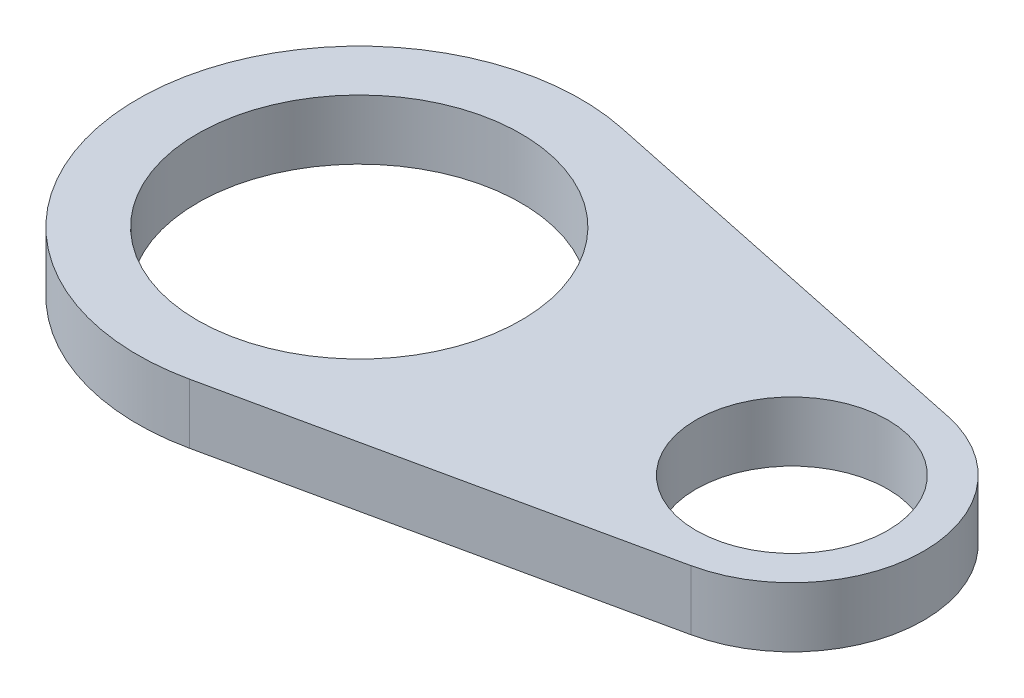
SolidWorks part; units mm, degrees
ref_plane "Front Plane" through (0, 0, 0) normal (0, 0, 1) x (1, 0, 0)
ref_plane "Top Plane" through (0, 0, 0) normal (0, 1, 0) x (1, 0, 0)
ref_plane "Right Plane" through (0, 0, 0) normal (1, 0, 0) x (0, 0, -1)
sketch "Sketch2" plane through (0, 0, 0) normal (0, 1, 0) x (1, 0, 0)
  circle A0 centre (0, 0) radius 18.5
  circle A1 centre (0, 0) radius 13.5
extrude "Boss-Extrude2" add sketch "Sketch2" along normal blind 5
sketch "Sketch3" plane through (0, 5, 0) normal (0, 1, 0) x (1, 0, 0)
  line L1 (25.4604, 0) -> (25.4604, 3.127)
  line L2 (25.4604, 3.127) -> (25.4604, -2.892)
  line L3 (25.4604, -2.892) -> (18.2726, -2.892)
  line L4 (18.2726, -2.892) -> (18.2726, 2.892)
  line L5 (18.2726, 2.892) -> (25.4604, 3.127)
  circle A0 centre (0, 0) radius 18.5 construction
extrude "Boss-Extrude3" add sketch "Sketch3" against normal blind 5 contours L2 L3 L4 L5
sketch "Sketch4" plane through (0, 5, 0) normal (0, 1, 0) x (1, 0, 0)
  circle A0 centre (36, 0.1175) radius 11
extrude "Boss-Extrude4" add sketch "Sketch4" against normal blind 5
sketch "Sketch5" plane through (0, 5, 0) normal (0, 1, 0) x (1, 0, 0)
  circle A0 centre (36, 0.1175) radius 8
extrude "Cut-Extrude1" cut sketch "Sketch5" against normal blind 5
sketch "Sketch6" plane through (0, 5, 0) normal (0, 1, 0) x (1, 0, 0)
  line L0 (38.2565, 10.8835) -> (3.7951, 18.1066)
  line L1 (3.7951, 18.1066) -> (18.2726, 2.892)
  line L2 (18.2726, 2.892) -> (25.4193, 3.1256)
  line L3 (25.4193, 3.1256) -> (38.2565, 10.8835)
  arc A0 (25.4197, -2.892) -> (25.4193, 3.1256) centre (36, 0.1175) ccw construction
  arc A1 (18.2726, 2.892) -> (18.2726, -2.892) centre (0, 0) ccw construction
extrude "Boss-Extrude5" add sketch "Sketch6" against normal blind 5
sketch "Sketch7" plane through (0, 5, 0) normal (0, 1, 0) x (1, 0, 0)
  line L0 (38.3268, -10.6336) -> (3.9132, -18.0814)
  line L1 (3.9132, -18.0814) -> (18.2726, -2.892)
  line L2 (18.2726, -2.892) -> (25.4197, -2.892)
  line L3 (25.4197, -2.892) -> (38.3268, -10.6336)
  arc A0 (25.4197, -2.892) -> (38.2565, 10.8835) centre (36, 0.1175) ccw construction
  arc A1 (3.7951, 18.1066) -> (18.2726, -2.892) centre (0, 0) ccw construction
extrude "Boss-Extrude6" add sketch "Sketch7" against normal blind 5
